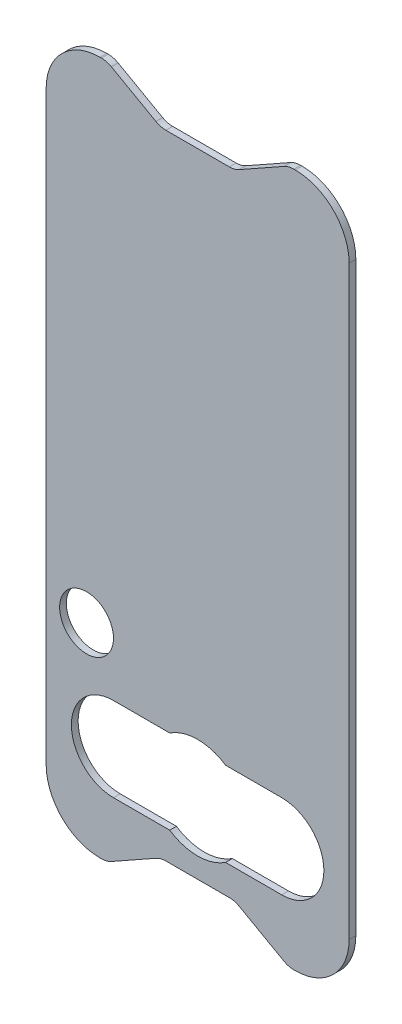
SolidWorks part; units mm, degrees
ref_plane "Front Plane" through (0, 0, 0) normal (0, 0, 1) x (1, 0, 0)
ref_plane "Top Plane" through (0, 0, 0) normal (0, 1, 0) x (1, 0, 0)
ref_plane "Right Plane" through (0, 0, 0) normal (1, 0, 0) x (0, 0, -1)
sketch "Sketch1" plane through (0, 0, 0) normal (0, 0, 1) x (1, 0, 0)
  line L0 (22.5, 0) -> (22.5, 15) construction
  line L1 (0, 0) -> (45, 0)
  line L2 (0, 0) -> (0, 103)
  line L3 (0, 103) -> (45, 103)
  line L4 (45, 0) -> (45, 103)
  line L5 (0, 0) -> (45, 103) construction
  line L6 (0, 103) -> (45, 0) construction
  line L7 (22.5, 15) -> (22.5, 15.9942) construction
  line L8 (22.5, 15.9942) -> (22.5, 95.7862) construction
  line L9 (22.5, 95.7862) -> (22.5, 100.0176) construction
  line L10 (22.5, 100.0176) -> (22.5, 103) construction
  line L11 (10.75, 15) -> (34.25, 15) construction
  line L12 (10.75, 22.25) -> (34.25, 22.25)
  line L13 (10.75, 7.75) -> (34.25, 7.75)
  line L14 (16.0128, 22.25) -> (16.0128, 7.75) construction
  line L15 (3.5, 15) -> (3.5, 25.5242) construction
  line L16 (3.5, 25.5242) -> (41.5, 25.5242) construction
  line L17 (41.5, 25.5242) -> (41.5, 15) construction
  arc A0 (10.75, 22.25) -> (10.75, 7.75) centre (10.75, 15) ccw
  arc A1 (34.25, 7.75) -> (34.25, 22.25) centre (34.25, 15) ccw
  point P4 (22.5, 51.5)
  point P14 (22.5, 15)
  dimension "D1" = 45
  dimension "D2" = 103
  dimension "D3" = 15
  dimension "D4" = 14.5
  dimension "D5" = 38
extrude "Boss-Extrude1" add sketch "Sketch1" along normal blind 1
fillet "Fillet1" radius 8 4 edges at (0, 0, 0.5) (45, 0, 0.5) (45, 103, 0.5) (0, 103, 0.5)
sketch "Sketch2" plane through (0, 0, 1) normal (0, 0, 1) x (1, 0, 0)
  line L0 (22.5, 0) -> (22.5, 29.25) construction
  line L1 (8, 0) -> (37, 0) construction
  line L2 (22.5, 29.25) -> (22.5, 102.6211) construction
  line L3 (22.5, 29.25) -> (6, 29.25) construction
  circle A0 centre (6, 29.25) radius 4
  dimension "D1" = 8
  dimension "D2" = 29.25
  dimension "D3" = 16.5
extrude "Cut-Extrude1" cut sketch "Sketch2" against normal blind 1
sketch "Sketch3" plane through (0, 0, 1) normal (0, 0, 1) x (1, 0, 0)
  line L0 (22.5, 0) -> (22.5, 4.5) construction
  line L1 (8, 0) -> (37, 0) construction
  line L2 (22.5, 4.5) -> (22.5, 98.5) construction
  line L3 (3.5, 15) -> (41.5, 15) construction
  line L4 (22.5, 98.5) -> (22.5, 103) construction
  line L5 (37, 103) -> (8, 103) construction
  line L6 (0, 51.5) -> (22.5, 51.5) construction
  line L7 (0, 95) -> (0, 8) construction
  line L8 (22.5, 51.5) -> (45, 51.5) construction
  line L9 (45, 8) -> (45, 95) construction
  line L10 (17, 98.5) -> (28, 98.5)
  line L11 (17, 4.5) -> (28, 4.5)
  line L12 (9, 0) -> (36, 0)
  line L13 (9, 103) -> (36, 103)
  line L14 (9, 103) -> (17, 98.5)
  line L15 (36, 103) -> (28, 98.5)
  line L16 (17, 4.5) -> (9, 0)
  line L17 (28, 4.5) -> (36, 0)
  line L18 (17, 4.5) -> (17, 15) construction
  arc A0 (10.75, 22.25) -> (10.75, 7.75) centre (10.75, 15) ccw construction
  arc A1 (34.25, 7.75) -> (34.25, 22.25) centre (34.25, 15) ccw construction
  point P18 (22.5, 98.5)
  point P21 (22.5, 4.5)
  point P24 (22.5, 0)
  point P27 (22.5, 103)
  point P31 (22.5, 51.5)
  dimension "D1" = 11
  dimension "D2" = 27
  dimension "D3" = 94
  dimension "D4" = 10.5
extrude "Cut-Extrude2" cut sketch "Sketch3" against normal blind 1
sketch "Sketch4" plane through (0, 0, 1) normal (0, 0, 1) x (1, 0, 0)
  line L0 (10, 15) -> (22.5, 15) construction
  line L1 (22.5, 15) -> (35, 15) construction
  line L2 (10, 21.25) -> (18.3542, 21.25)
  line L3 (26.6458, 21.25) -> (35, 21.25)
  line L4 (34.25, 22.25) -> (10.75, 22.25) construction
  line L7 (22.5, 22.25) -> (22.5, 15) construction
  line L8 (10, 21.25) -> (35, 21.25) construction
  line L9 (10, 8.75) -> (35, 8.75) construction
  line L14 (22.5, 15) -> (22.5, 7.5) construction
  line L16 (22.5, 22.25) -> (22.5, 98.5) construction
  line L18 (10, 8.75) -> (18.3542, 8.75)
  line L19 (26.6458, 8.75) -> (35, 8.75)
  line L20 (9.6072, 15) -> (35.3928, 15) construction
  line L21 (9.6072, 23.8124) -> (35.3928, 23.8124)
  line L22 (9.6072, 6.1876) -> (35.3928, 6.1876)
  circle A5 centre (10, 15) radius 6.25 construction
  circle A6 centre (35, 15) radius 6.25 construction
  arc A11 (18.3542, 21.25) -> (26.6458, 21.25) centre (22.5, 15) cw
  circle A13 centre (22.5, 15) radius 7.5 construction
  arc A14 (18.3542, 8.75) -> (26.6458, 8.75) centre (22.5, 15) ccw
  arc A15 (10, 21.25) -> (10, 8.75) centre (10, 15) ccw
  arc A16 (35, 21.25) -> (35, 8.75) centre (35, 15) cw
  arc A17 (9.6072, 23.8124) -> (9.6072, 6.1876) centre (9.6072, 15) ccw
  arc A18 (35.3928, 6.1876) -> (35.3928, 23.8124) centre (35.3928, 15) ccw
  point P4 (22.5, 15)
  dimension "D2" = 12.5
  dimension "D3" = 12.5
  dimension "D1" = 15
extrude "Boss-Extrude2" add sketch "Sketch4" against normal up to vertex (1 mm away)
sketch "Sketch5" plane through (0, 0, 1) normal (0, 0, 1) x (1, 0, 0)
  line L0 (3.75, 15) -> (41.25, 15) construction
  arc A0 (10, 21.25) -> (10, 8.75) centre (10, 15) ccw construction
  arc A1 (35, 8.75) -> (35, 21.25) centre (35, 15) ccw construction
  circle A2 centre (22.5, 15) radius 7.5
  dimension "D1" = 15
extrude "Cut-Extrude3" cut sketch "Sketch5" against normal blind 10
fillet "Fillet2" radius 3 8 edges at (28, 4.5, 0.5) (17, 4.5, 0.5) (9, 0, 0.5) (36, 0, 0.5) (36, 103, 0.5) (28, 98.5, 0.5) (17, 98.5, 0.5) (9, 103, 0.5)
